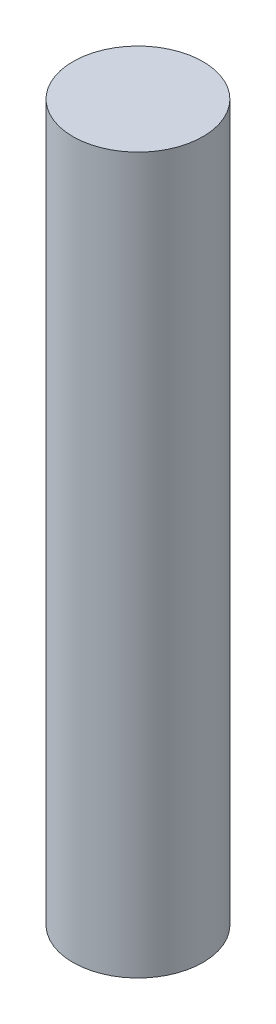
SolidWorks part; units mm, degrees
ref_plane "Front Plane" through (0, 0, 0) normal (0, 0, 1) x (1, 0, 0)
ref_plane "Top Plane" through (0, 0, 0) normal (0, 1, 0) x (1, 0, 0)
ref_plane "Right Plane" through (0, 0, 0) normal (1, 0, 0) x (0, 0, -1)
sketch "Sketch1" plane through (0, 0, 0) normal (0, 1, 0) x (1, 0, 0)
  circle A0 centre (0, 0) radius 2
  dimension "D1" = 4
extrude "Boss-Extrude1" add sketch "Sketch1" along normal blind 22 contours A0
